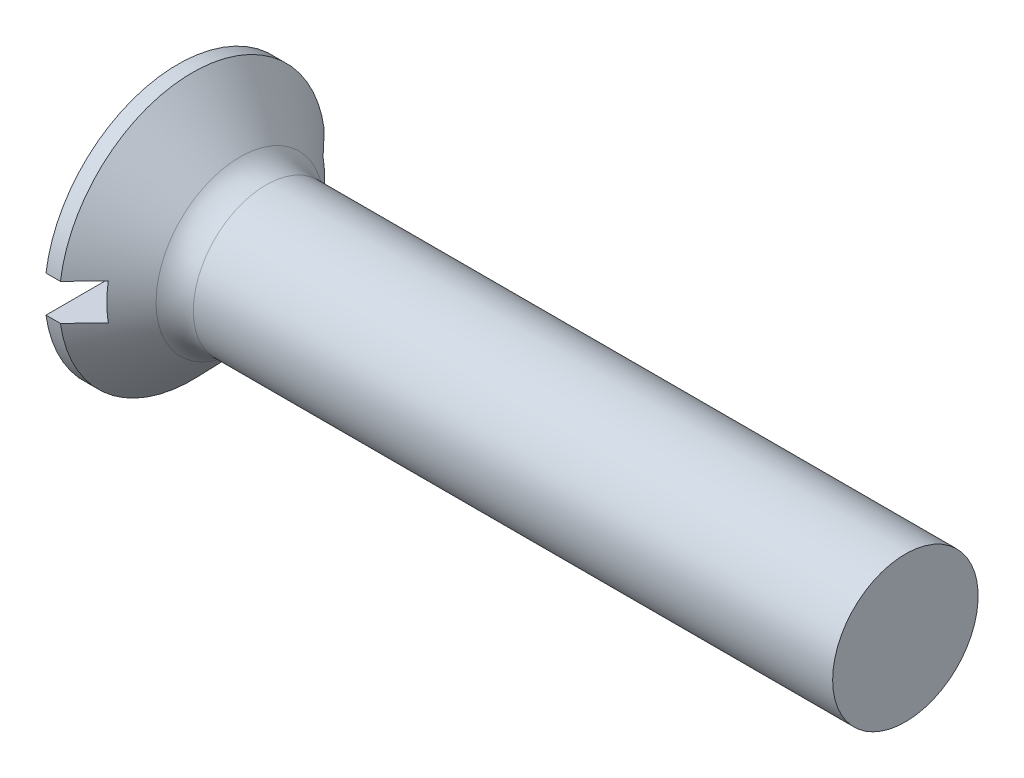
SolidWorks part; units mm, degrees
revolve "Base-Revolve" add sketch "BodySke" angle 360 about L5
sketch "BodySke" plane through (0, 0, 0) normal (0, 0, 1) x (1, 0, 0)
  line L0 (0, 0) -> (0, 9.15)
  line L1 (0, 9.15) -> (0.9924, 9.15)
  line L2 (5, 5) -> (50, 5)
  line L3 (50, 5) -> (50, 0)
  line L4 (50, 0) -> (0, 0)
  line L5 (-6.35, 0) -> (82.55, 0) construction
  line L6 (5, -5) -> (50, -5) construction
  line L7 (0.9924, -9.15) -> (5, -5) construction
  line L8 (0.9924, 9.15) -> (5, 5)
  line L9 (0, -9.15) -> (0.9924, -9.15) construction
  line L10 (6.5, 6.5875) -> (6.5, -2.9375) construction
  line L11 (0, 6.35) -> (0, -3.175) construction
  dimension "Length" = 50
  dimension "Thread_nom" = 50
cosmetic thread "ThreadCosmetic" [suppressed] parameters "Thread_length"=3.4, "Thread_minor"=7.9248
extrude "Slot" cut sketch "Sketch2" against normal blind 2.6
sketch "Sketch2" plane through (0, 0, 0) normal (-1, 0, 0) x (0, 0, 1)
  line L0 (-9.15, -1.25) -> (9.15, -1.25)
  line L1 (-9.15, -1.25) -> (-9.15, 1.25)
  line L2 (9.15, 1.25) -> (-9.15, 1.25)
  line L3 (9.15, 1.25) -> (9.15, -1.25)
  dimension "D1" = 0.25
  dimension "D2" = 3.8
  dimension "D3" = 1.9
ref_plane "Plane1" through (0, 0, 0) normal (0, 0, 1) x (1, 0, 0)
ref_plane "Plane2" through (0, 0, 0) normal (0, 1, 0) x (1, 0, 0)
ref_plane "Plane3" through (0, 0, 0) normal (1, 0, 0) x (0, 0, -1)
other "Configuration Table"
fillet "Fillet1" radius 2.5 1 edges at (5, 0, 5)
sketch "ThdSchSke" plane through (0, 0, 0) normal (0, 0, 1) x (1, 0, 0)
  line L0 (6.5, -3.9624) -> (5.7735, -5)
  line L1 (6.5, -3.9624) -> (7.2265, -5)
  line L2 (7.2265, -5) -> (7.2265, -6.25)
  line L3 (-3.175, 0) -> (5.1513, 0) construction
  line L5 (7.2265, -6.25) -> (5.7735, -6.25)
  line L6 (5.7735, -6.25) -> (5.7735, -5)
  line L7 (0, 9.15) -> (0, 1.25) construction
  dimension "Thread_minor" = 1.548
  dimension "Diameter" = 2
  dimension "Start" = 1.6
revolve "ThreadSchematic" [suppressed] cut sketch "ThdSchSke" angle 360 about L3
pattern_linear "ThdSchPat" [suppressed]
equation "\"D1@Sketch2\" = \"Slot_width@Sketch2\" / 2"
equation "\"D2@Sketch2\" = \"Head_dia@BodySke\""
equation "\"D3@Sketch2\" = \"D2@Sketch2\" / 2"
equation "\"Thread_length@ThreadCosmetic\" = ((sgn( (\"Length@BodySke\" - \"Advance@BodySke\" * 1.0 - \"Head_ht@BodySke\" ) - \"Thread_nom@BodySke\" )-1)*( (\"Length@BodySke\" - \"Advance@BodySke\" * 1.0 - \"Head_ht@BodySke\" ) - \"Thread_nom@BodySke\" ))/-2+ \"Thread_nom@BodySke\""
equation "\"Thread_minor@ThdSchSke\" = \"Thread_minor@ThreadCosmetic\""
equation "\"Diameter@ThdSchSke\" = \"Diameter@BodySke\""
equation "\"Overcut@ThdSchSke\" = \"Diameter@BodySke\" * 1.25"
equation "\"Start@ThdSchSke\" = 0.000001 + \"Length@BodySke\" - \"Thread_length@ThreadCosmetic\"  '---Countersunk---"
equation "\"Num_threads@ThdSchPat\" = int( \"Thread_length@ThreadCosmetic\" / \"Advance@BodySke\" + 0.999 )  + 1"
equation "\"Advance@ThdSchPat\" = \"Thread_length@ThreadCosmetic\" /  (\"Num_threads@ThdSchPat\" - 1) 'relax it"
